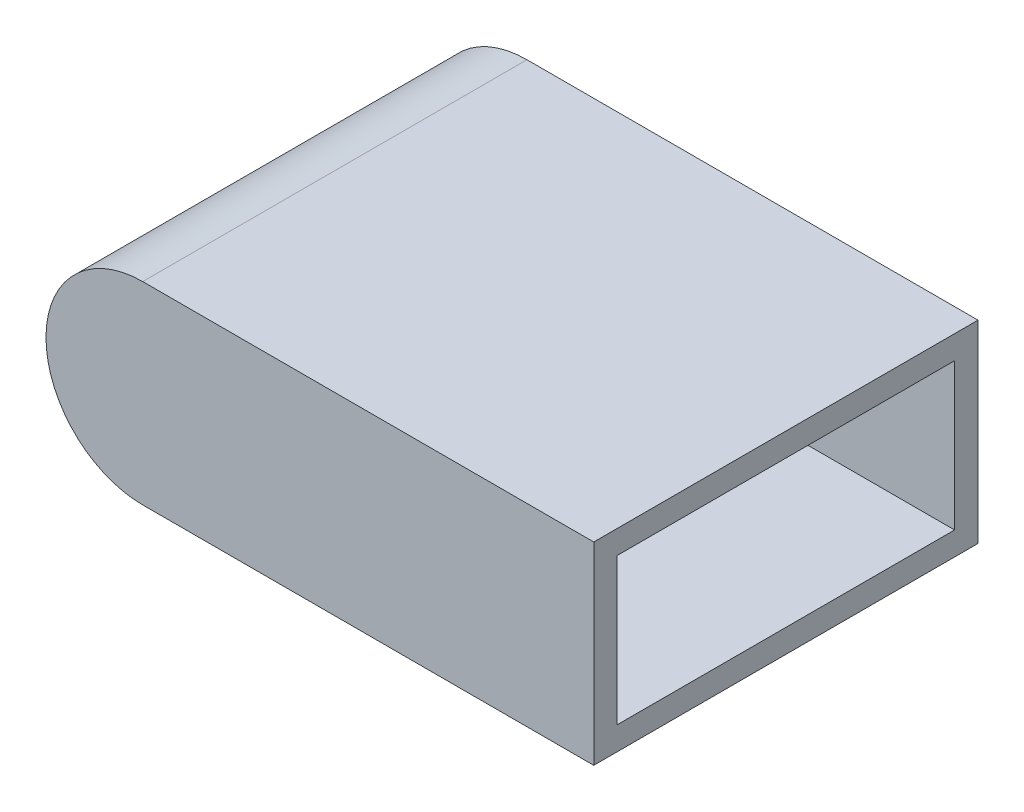
SolidWorks part; units mm, degrees
ref_plane "Plan de face" through (0, 0, 0) normal (0, 0, 1) x (1, 0, 0)
ref_plane "Plan de dessus" through (0, 0, 0) normal (0, 1, 0) x (1, 0, 0)
ref_plane "Plan de droite" through (0, 0, 0) normal (1, 0, 0) x (0, 0, -1)
sketch "Esquisse1" plane through (0, 0, 0) normal (0, 1, 0) x (1, 0, 0)
  line L1 (18.2408, 22.15) -> (-33.7592, 22.15)
  line L2 (18.2408, 22.15) -> (18.2408, -22.15)
  line L3 (18.2408, -22.15) -> (-33.7592, -22.15)
  line L4 (-33.7592, 22.15) -> (-33.7592, -22.15)
  line L5 (18.2408, 22.15) -> (-33.7592, -22.15) construction
  line L6 (18.2408, -22.15) -> (-33.7592, 22.15) construction
  point P0 (-7.7592, 0)
  dimension "D1" = 44.3
  dimension "D2" = 52
extrude "Boss.-Extru.1" add sketch "Esquisse1" along normal blind 22.3
sketch "Esquisse4" plane through (18.2408, 0, 0) normal (1, 0, 0) x (0, 0, -1)
  line L0 (-22.15, 22.3) -> (22.15, 0) construction
  line L1 (22.15, 22.3) -> (22.15, 0) construction
  line L2 (-19.45, 2.7) -> (19.45, 2.7)
  line L3 (-19.45, 2.7) -> (-19.45, 19.6)
  line L4 (-19.45, 19.6) -> (19.45, 19.6)
  line L5 (19.45, 2.7) -> (19.45, 19.6)
  line L6 (-19.45, 2.7) -> (19.45, 19.6) construction
  line L7 (-19.45, 19.6) -> (19.45, 2.7) construction
  line L8 (-22.15, 22.3) -> (22.15, 22.3) construction
  point P4 (0, 11.15)
  point P13 (0, 22.3)
  dimension "D1" = 2.7
  dimension "D2" = 2.7
extrude "Enlèv. mat.-Extru.2" cut sketch "Esquisse4" against normal up to vertex (52 mm away)
sketch "Esquisse5" plane through (0, 0, 22.15) normal (0, 0, 1) x (1, 0, 0)
  line L0 (-33.7592, 22.3) -> (-33.7592, 0) construction
  line L5 (-33.7592, 0) -> (18.2408, 0)
  line L6 (18.2408, 0) -> (18.2408, 22.3)
  line L7 (18.2408, 22.3) -> (-33.7592, 22.3)
  line L8 (-33.7592, 22.3) -> (-33.7592, 0)
  line L12 (-33.7592, 22.3) -> (-33.7592, 0)
  arc A0 (-33.7592, 22.3) -> (-33.7592, 0) centre (-33.7592, 11.15) ccw
  dimension "D1" = 0
extrude "Boss.-Extru.3" add sketch "Esquisse5" against normal up to vertex (44.3 mm away)
sketch "Esquisse8" plane through (0, 0, 19.45) normal (0, 0, -1) x (-1, 0, 0)
  line L0 (-18.2408, 11.15) -> (33.7592, 11.15) construction
  line L1 (-18.2408, 19.6) -> (-18.2408, 2.7) construction
  line L2 (33.7592, 19.6) -> (33.7592, 2.7) construction
  line L3 (33.7592, 2.7) -> (33.7592, 19.6)
  arc A0 (33.7592, 2.7) -> (33.7592, 19.6) centre (33.7592, 11.15) ccw
extrude "Enlèv. mat.-Extru.4" cut sketch "Esquisse8" along normal up to vertex (38.9 mm away)
